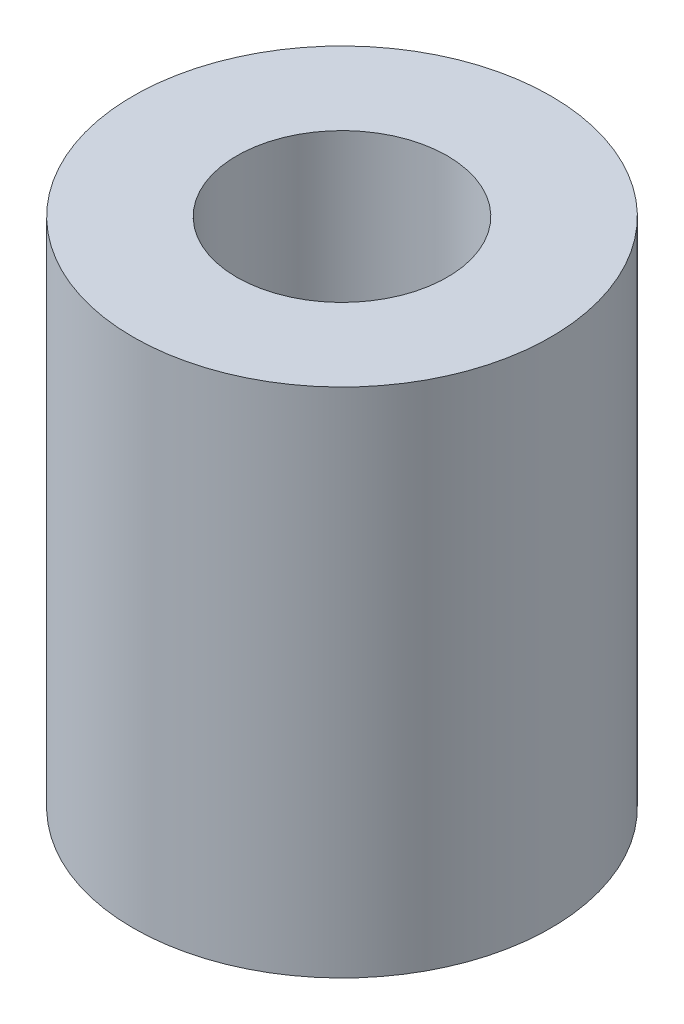
SolidWorks part; units mm, degrees
ref_plane "Front Plane" through (0, 0, 0) normal (0, 0, 1) x (1, 0, 0)
ref_plane "Top Plane" through (0, 0, 0) normal (0, 1, 0) x (1, 0, 0)
ref_plane "Right Plane" through (0, 0, 0) normal (1, 0, 0) x (0, 0, -1)
sketch "Sketch1" plane through (0, 0, 0) normal (0, 1, 0) x (1, 0, 0)
  circle A0 centre (0, 0) radius 7.9375
  dimension "D1" = 15.875
extrude "Boss-Extrude1" add sketch "Sketch1" along normal blind 19.45
sketch "Sketch2" plane through (0, 19.45, 0) normal (0, 1, 0) x (1, 0, 0)
  circle A0 centre (0, 0) radius 4
  dimension "D1" = 8
sketch "Sketch3" plane through (0, 19.45, 0) normal (0, 1, 0) x (1, 0, 0)
  circle A0 centre (0, 0) radius 4
  dimension "D1" = 8
extrude "Cut-Extrude2" cut sketch "Sketch3" against normal through all
